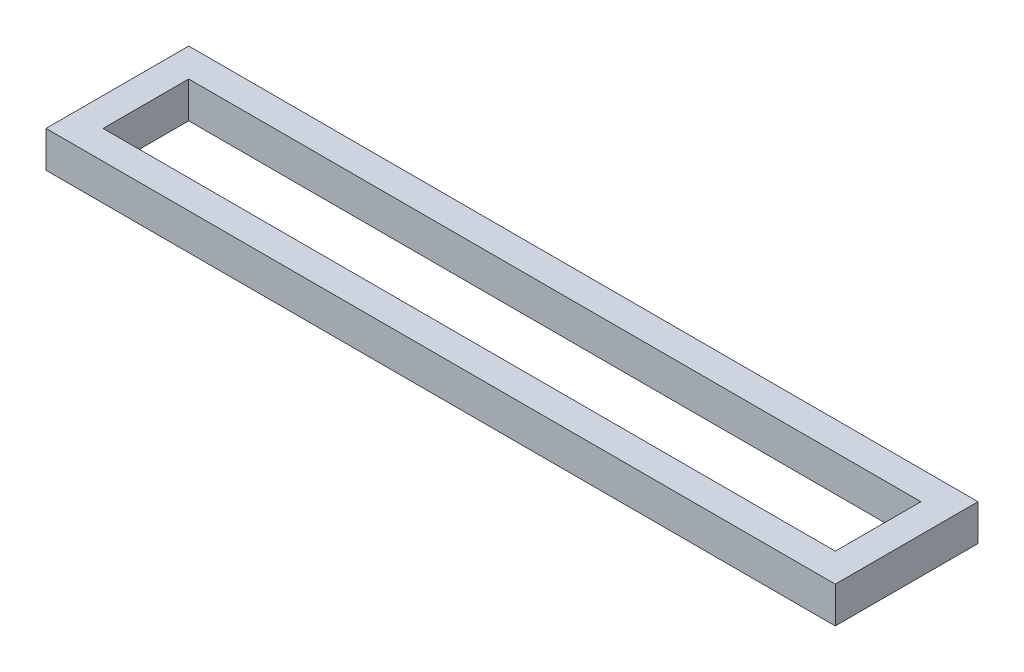
SolidWorks part; units mm, degrees
ref_plane "Front Plane" through (0, 0, 0) normal (0, 0, 1) x (1, 0, 0)
ref_plane "Top Plane" through (0, 0, 0) normal (0, 1, 0) x (1, 0, 0)
ref_plane "Right Plane" through (0, 0, 0) normal (1, 0, 0) x (0, 0, -1)
sketch "Sketch1" plane through (0, 0, 0) normal (0, 1, 0) x (1, 0, 0)
  line L0 (-5, 20) -> (133.25, 20)
  line L1 (0, 0) -> (128.25, 0)
  line L2 (0, 0) -> (0, 15)
  line L3 (0, 15) -> (128.25, 15)
  line L4 (128.25, 0) -> (128.25, 15)
  line L5 (133.25, -5) -> (133.25, 20)
  line L6 (-5, -5) -> (133.25, -5)
  line L7 (-5, -5) -> (-5, 20)
  dimension "D1" = 15
  dimension "D2" = 128.25
  dimension "D3" = 5
extrude "Boss-Extrude1" add sketch "Sketch1" along normal blind 6.35
